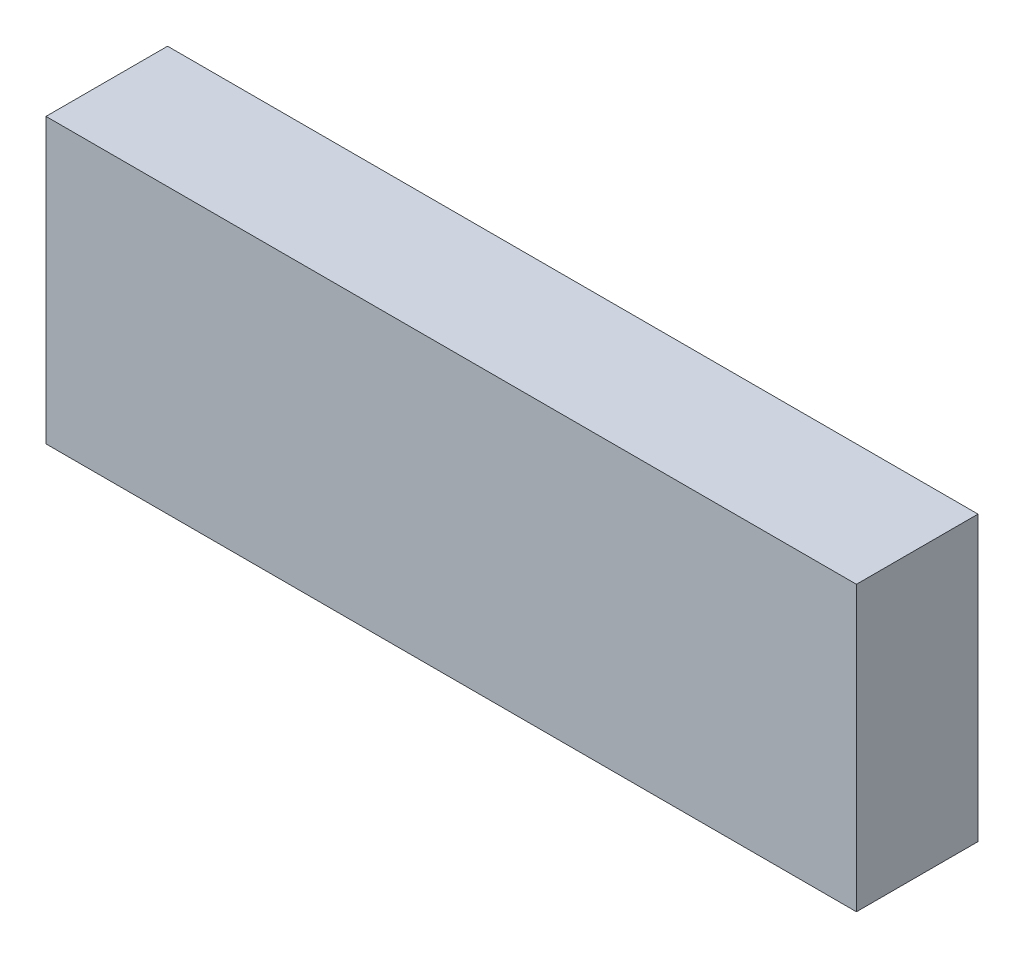
SolidWorks part; units mm, degrees
ref_plane "Front Plane" through (0, 0, 0) normal (0, 0, 1) x (1, 0, 0)
ref_plane "Top Plane" through (0, 0, 0) normal (0, 1, 0) x (1, 0, 0)
ref_plane "Right Plane" through (0, 0, 0) normal (1, 0, 0) x (0, 0, -1)
sketch "Sketch1" plane through (0, 0, 0) normal (1, 0, 0) x (0, 0, -1)
  line L1 (-19.05, -44.45) -> (19.05, -44.45)
  line L2 (-19.05, -44.45) -> (-19.05, 44.45)
  line L3 (-19.05, 44.45) -> (19.05, 44.45)
  line L4 (19.05, -44.45) -> (19.05, 44.45)
  line L5 (-19.05, -44.45) -> (19.05, 44.45) construction
  line L6 (-19.05, 44.45) -> (19.05, -44.45) construction
  point P0 (0, 0)
  dimension "D1" = 38.1
  dimension "D2" = 88.9
extrude "Boss-Extrude1" add sketch "Sketch1" along normal blind 254
